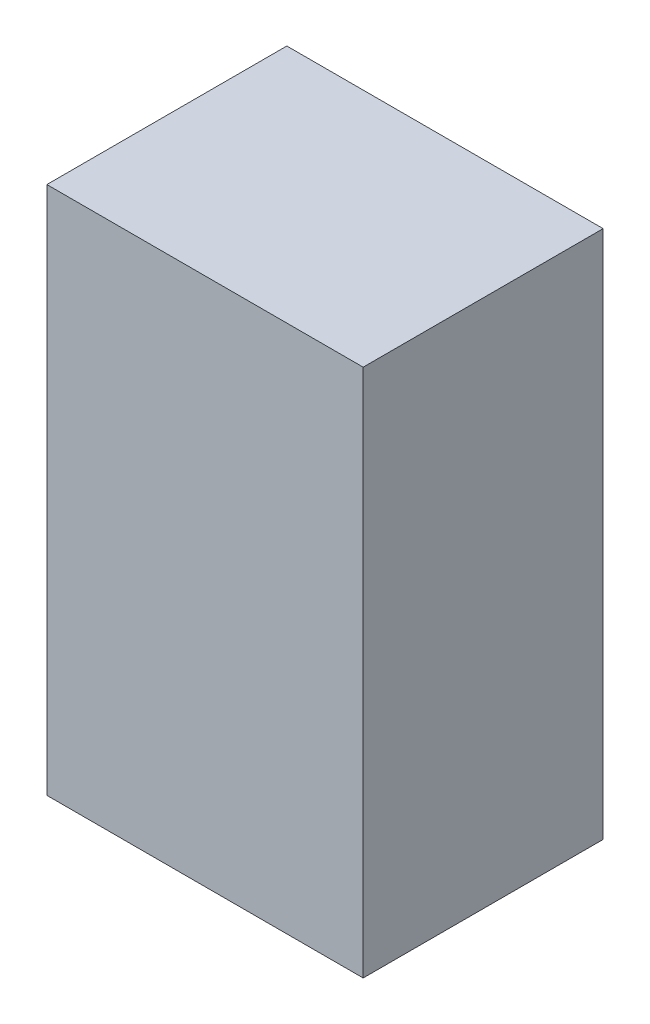
SolidWorks part; units mm, degrees
ref_plane "Plan de face" through (0, 0, 0) normal (0, 0, 1) x (1, 0, 0)
ref_plane "Plan de dessus" through (0, 0, 0) normal (0, 1, 0) x (1, 0, 0)
ref_plane "Plan de droite" through (0, 0, 0) normal (1, 0, 0) x (0, 0, -1)
sketch "Esquisse1" plane through (0, 0, 0) normal (0, 1, 0) x (1, 0, 0)
  line L1 (29, 22) -> (-29, 22)
  line L2 (29, 22) -> (29, -22)
  line L3 (29, -22) -> (-29, -22)
  line L4 (-29, 22) -> (-29, -22)
  line L5 (29, 22) -> (-29, -22) construction
  line L6 (29, -22) -> (-29, 22) construction
  point P0 (0, 0)
extrude "Boss.-Extru.1" add sketch "Esquisse1" along normal blind 97
